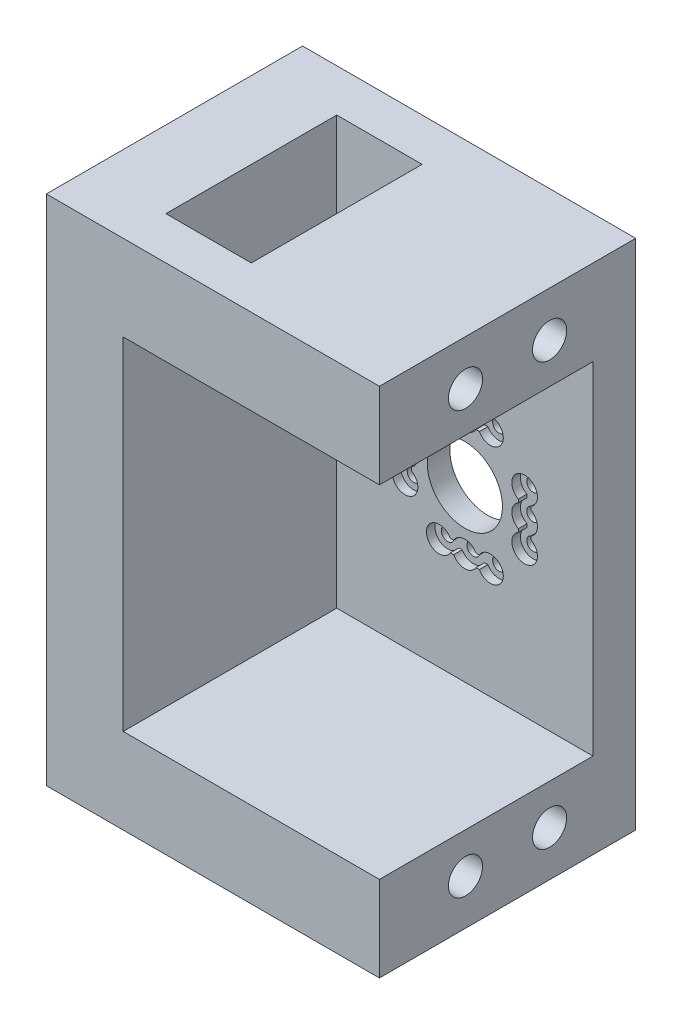
SolidWorks part; units mm, degrees
material "ABS"
ref_plane "Front Plane" through (0, 0, 0) normal (0, 0, 1) x (1, 0, 0)
ref_plane "Top Plane" through (0, 0, 0) normal (0, 1, 0) x (1, 0, 0)
ref_plane "Right Plane" through (0, 0, 0) normal (1, 0, 0) x (0, 0, -1)
sketch "Sketch1" plane through (0, 0, 0) normal (1, 0, 0) x (0, 0, -1)
  line L1 (-15, -30) -> (15, -30)
  line L2 (-15, -30) -> (-15, 30)
  line L3 (-15, 30) -> (15, 30)
  line L4 (15, -30) -> (15, 30)
  line L5 (-15, -30) -> (15, 30) construction
  line L6 (-15, 30) -> (15, -30) construction
  point P0 (0, 0)
  dimension "D1" = 30
  dimension "D2" = 60
extrude "Boss-Extrude1" add sketch "Sketch1" along normal blind 39
sketch "Sketch2" plane through (39, 0, 0) normal (1, 0, 0) x (0, 0, -1)
  line L1 (-10, 20) -> (10, 20)
  line L2 (-10, 20) -> (-10, -20)
  line L3 (-10, -20) -> (10, -20)
  line L4 (10, 20) -> (10, -20)
  line L5 (-10, 20) -> (10, -20) construction
  line L6 (-10, -20) -> (10, 20) construction
  point P0 (0, 0)
  dimension "D1" = 20
  dimension "D2" = 40
extrude "Cut-Extrude1" cut sketch "Sketch2" against normal blind 30
sketch "Sketch3" plane through (0, 20, 0) normal (0, -1, 0) x (1, 0, 0)
  line L0 (9, -10) -> (39, -10) construction
  line L1 (9, 10) -> (19, 10)
  line L2 (9, 10) -> (9, -10)
  line L3 (9, -10) -> (19, -10)
  line L4 (19, 10) -> (19, -10)
  dimension "D1" = 10
extrude "Cut-Extrude2" cut sketch "Sketch3" against normal up to surface (10 mm away) up to face at (19.5, 30, 0)
sketch "Sketch4" plane through (39, 0, 0) normal (1, 0, 0) x (0, 0, -1)
  line L0 (15, 30) -> (-15, 30) construction
  line L2 (0, 30) -> (0, 0) construction
  line L3 (0, 0) -> (15, 0) construction
  line L4 (15, -30) -> (15, 30) construction
  circle A0 centre (4.925, 24.71) radius 2
  circle A1 centre (-4.925, 24.71) radius 2
  circle A2 centre (4.925, -24.71) radius 2
  circle A3 centre (-4.925, -24.71) radius 2
  point P5 (0, 30)
  dimension "D1" = 4
  dimension "D2" = 5.29
  dimension "D3" = 4.925
extrude "Cut-Extrude3" cut sketch "Sketch4" against normal blind 15
sketch "Sketch5" plane through (0, 0, -10) normal (0, 0, 1) x (1, 0, 0)
  line L1 (19, 20) -> (39, 20) construction
  line L4 (39, -20) -> (39, 20) construction
  circle A0 centre (24, 0) radius 10.35
  dimension "D2" = 20.7
  dimension "D1" = 20
  dimension "D3" = 15
extrude "Cut-Extrude4" cut sketch "Sketch5" against normal up to surface (2.35 mm away) from offset 2.65 up to face at (19.5, 0, -15) offset against normal yes
sketch "Sketch6" plane through (39, 0, 0) normal (1, 0, 0) x (0, 0, -1)
  line L0 (-15, 30) -> (-15, -30) construction
  line L1 (-10, 20) -> (-15, 20)
  line L2 (-10, 20) -> (-10, -20)
  line L3 (-10, -20) -> (-15, -20)
  line L4 (-15, 20) -> (-15, -20)
  line L5 (-10, -20) -> (10, -20) construction
  dimension "D1" = 0
extrude "Cut-Extrude5" cut sketch "Sketch6" against normal up to surface (30 mm away) up to face at (9, 5, 0)
sketch "Sketch7" plane through (0, 0, -12.65) normal (0, 0, -1) x (-1, 0, 0)
  circle A0 centre (-24, 0) radius 4.4
extrude "Cut-Extrude6" cut sketch "Sketch7" against normal up to surface (2.65 mm away) up to face at (22.3333, 10, -10)
sketch "Sketch8" plane through (0, 0, -10) normal (0, 0, 1) x (1, 0, 0)
  line L2 (9, -20) -> (39, -20) construction
  circle A0 centre (24, 7) radius 0.75
  circle A1 centre (24, 0) radius 4.4 construction
  circle A2 centre (27, 7) radius 0.75
  circle A4 centre (21, 7) radius 0.75
  circle A5 centre (31, 3) radius 0.75
  circle A6 centre (31, 0) radius 0.75
  circle A7 centre (31, -3) radius 0.75
  circle A8 centre (27, -7) radius 0.75
  circle A9 centre (24, -7) radius 0.75
  circle A10 centre (21, -7) radius 0.75
  circle A11 centre (17, -3) radius 0.75
  circle A12 centre (17, 0) radius 0.75
  circle A13 centre (17, 3) radius 0.75
  point P6 (24, -20)
  dimension "D1" = 1.5
  dimension "D3" = 1.5
  dimension "D6" = 1.5
  dimension "D2" = 7
  dimension "D4" = 3
  dimension "D5" = 3
  dimension "D7" = 4
extrude "Cut-Extrude7" cut sketch "Sketch8" against normal up to surface (2.65 mm away) up to face at (19.6, 0, -12.65)
sketch "Sketch9" plane through (0, 0, -10) normal (0, 0, 1) x (1, 0, 0)
  line L0 (22.3074, 7.7353) -> (22.6926, 7.7353)
  line L1 (25.3074, 7.7353) -> (25.6926, 7.7353)
  line L2 (22.305, 6.2604) -> (22.695, 6.2604)
  line L3 (25.305, 6.2604) -> (25.695, 6.2604)
  line L4 (30.2604, 1.695) -> (30.2604, 1.305)
  line L5 (30.2604, -1.305) -> (30.2604, -1.695)
  line L6 (31.7353, -1.3074) -> (31.7353, -1.6926)
  line L7 (31.7353, 1.6926) -> (31.7353, 1.3074)
  line L8 (25.695, -6.2604) -> (25.305, -6.2604)
  line L9 (22.695, -6.2604) -> (22.305, -6.2604)
  line L10 (22.6926, -7.7353) -> (22.3074, -7.7353)
  line L11 (25.6926, -7.7353) -> (25.3074, -7.7353)
  line L12 (17.7396, -1.695) -> (17.7396, -1.305)
  line L13 (17.7396, 1.305) -> (17.7396, 1.695)
  line L14 (16.2647, 1.3074) -> (16.2647, 1.6926)
  line L15 (16.2647, -1.6926) -> (16.2647, -1.3074)
  arc A0 (22.695, 6.2604) -> (25.305, 6.2604) centre (24, 7) ccw
  arc A1 (25.695, 6.2604) -> (25.6926, 7.7353) centre (27, 7) ccw
  arc A2 (22.3074, 7.7353) -> (22.305, 6.2604) centre (21, 7) ccw
  arc A12 (25.3074, 7.7353) -> (22.6926, 7.7353) centre (24, 7) ccw
  arc A13 (31.7353, 1.6926) -> (30.2604, 1.695) centre (31, 3) ccw
  arc A14 (30.2604, 1.305) -> (30.2604, -1.305) centre (31, 0) ccw
  arc A15 (30.2604, -1.695) -> (31.7353, -1.6926) centre (31, -3) ccw
  arc A16 (31.7353, -1.3074) -> (31.7353, 1.3074) centre (31, 0) ccw
  arc A17 (25.6926, -7.7353) -> (25.695, -6.2604) centre (27, -7) ccw
  arc A18 (25.305, -6.2604) -> (22.695, -6.2604) centre (24, -7) ccw
  arc A19 (22.305, -6.2604) -> (22.3074, -7.7353) centre (21, -7) ccw
  arc A20 (22.6926, -7.7353) -> (25.3074, -7.7353) centre (24, -7) ccw
  arc A21 (16.2647, -1.6926) -> (17.7396, -1.695) centre (17, -3) ccw
  arc A22 (17.7396, -1.305) -> (17.7396, 1.305) centre (17, 0) ccw
  arc A23 (17.7396, 1.695) -> (16.2647, 1.6926) centre (17, 3) ccw
  arc A24 (16.2647, 1.3074) -> (16.2647, -1.3074) centre (17, 0) ccw
  dimension "D1" = 3
  dimension "D2" = 3
  dimension "D3" = 3
  dimension "D5" = 0.39
  dimension "D6" = 0.3852
  dimension "D7" = 0.3852
  dimension "D8" = 0.39
  dimension "D4" = 4
extrude "Cut-Extrude10" cut sketch "Sketch9" against normal blind 1
